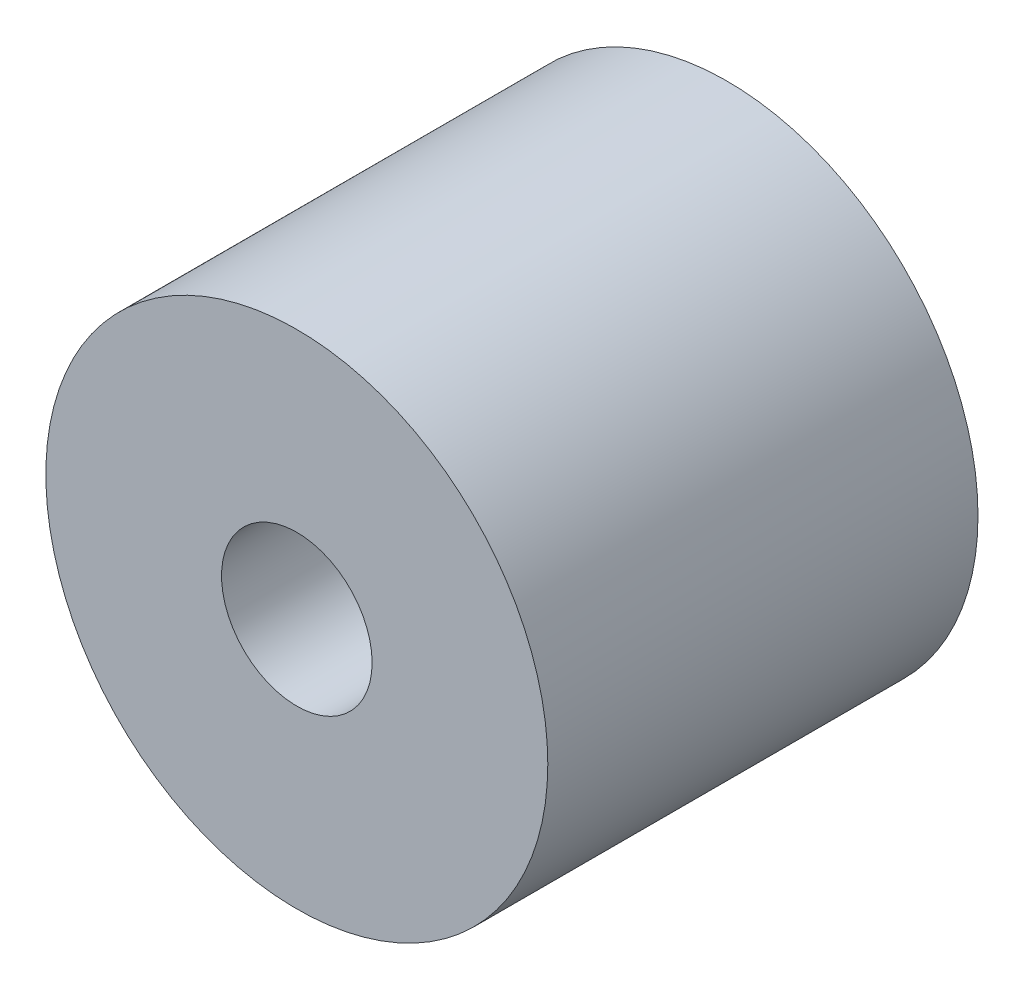
SolidWorks part; units mm, degrees
ref_plane "Front Plane" through (0, 0, 0) normal (0, 0, 1) x (1, 0, 0)
ref_plane "Top Plane" through (0, 0, 0) normal (0, 1, 0) x (1, 0, 0)
ref_plane "Right Plane" through (0, 0, 0) normal (1, 0, 0) x (0, 0, -1)
sketch "Sketch1" plane through (0, 0, 0) normal (0, 0, 1) x (1, 0, 0)
  circle A0 centre (0, 0) radius 7.5
  circle A1 centre (0, 0) radius 2.25
  dimension "D1" = 15
  dimension "D2" = 4.5
extrude "Boss-Extrude1" add sketch "Sketch1" along normal blind 12.855
